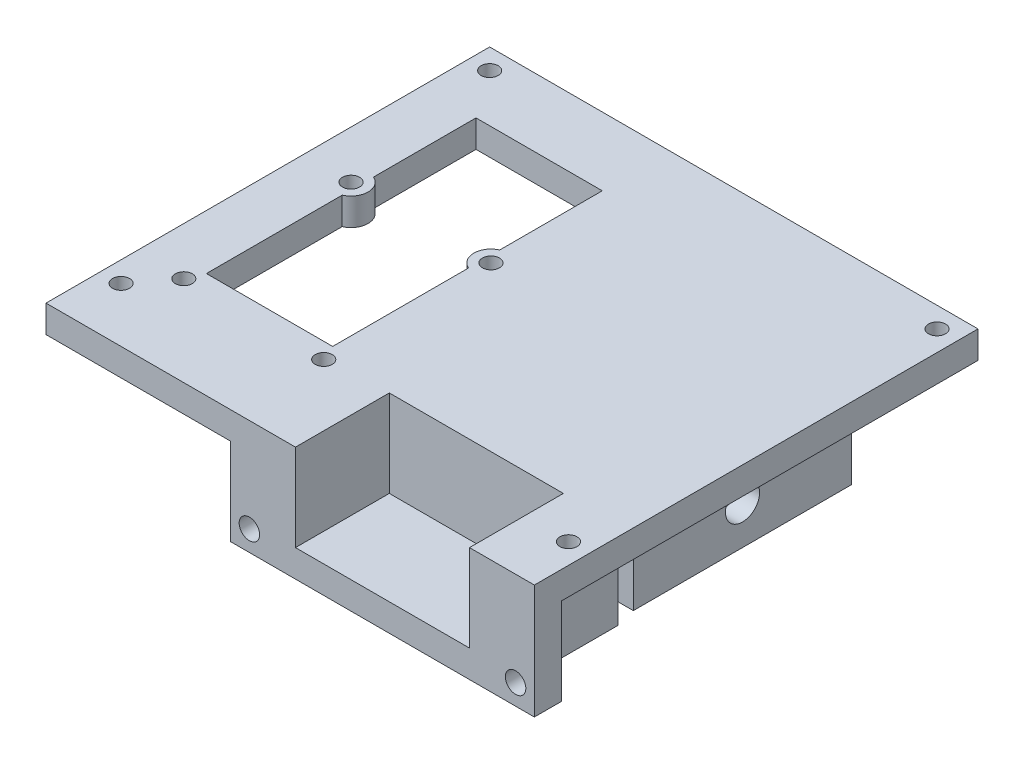
SolidWorks part; units mm, degrees
ref_plane "Front Plane" through (0, 0, 0) normal (0, 0, 1) x (1, 0, 0)
ref_plane "Top Plane" through (0, 0, 0) normal (0, 1, 0) x (1, 0, 0)
ref_plane "Right Plane" through (0, 0, 0) normal (1, 0, 0) x (0, 0, -1)
sketch "Sketch1" plane through (0, 0, 0) normal (0, 1, 0) x (1, 0, 0)
  line L1 (0, 0) -> (36.55, 0)
  line L2 (0, 0) -> (0, 65)
  line L4 (71.55, 0) -> (71.55, 65)
  line L9 (0, 65) -> (71.55, 65)
  line L11 (62.05, 0) -> (62.05, 13.75)
  line L12 (62.05, 13.75) -> (36.55, 13.75)
  line L13 (36.55, 0) -> (36.55, 13.75)
  line L14 (62.05, 0) -> (71.55, 0)
  dimension "D1" = 65
  dimension "D2" = 71.55
  dimension "D3" = 9.5
  dimension "D4" = 13.75
  dimension "D5" = 25.5
extrude "Boss-Extrude1" add sketch "Sketch1" along normal blind 4
sketch "Sketch2" plane through (0, 0, 0) normal (0, 1, 0) x (1, 0, 0)
  line L0 (62.05, 13.75) -> (62.05, 0) construction
  line L1 (36.55, 13.75) -> (62.05, 13.75) construction
  line L2 (36.55, 0) -> (36.55, 13.75) construction
  line L3 (62.05, 13.75) -> (62.05, 0)
  line L4 (36.55, 13.75) -> (62.05, 13.75)
  line L5 (36.55, 0) -> (36.55, 13.75)
  line L6 (32.55, 0) -> (32.55, 17.75)
  line L7 (32.55, 17.75) -> (66.05, 17.75)
  line L8 (66.05, 17.75) -> (66.05, 0)
  line L9 (36.55, 0) -> (32.55, 0)
  line L10 (62.05, 0) -> (66.05, 0)
  dimension "D1" = 4
extrude "Boss-Extrude2" add sketch "Sketch2" against normal blind 8.75
sketch "Sketch3" plane through (0, -8.75, 0) normal (0, -1, 0) x (1, 0, 0)
  line L1 (32.55, -17.75) -> (66.05, -17.75)
  line L2 (32.55, -17.75) -> (32.55, 0)
  line L3 (32.55, 0) -> (66.05, 0)
  line L4 (66.05, -17.75) -> (66.05, 0)
extrude "Boss-Extrude3" add sketch "Sketch3" along normal blind 4
sketch "Sketch4" plane through (0, 4, 0) normal (0, 1, 0) x (1, 0, 0)
  line L0 (0, 65) -> (0, 0) construction
  line L1 (8, 15.5) -> (26.5, 15.5)
  line L2 (8, 15.5) -> (8, 55)
  line L3 (8, 55) -> (26.5, 55)
  line L4 (26.5, 15.5) -> (26.5, 55)
  line L5 (71.55, 65) -> (0, 65) construction
  line L6 (0, 0) -> (36.55, 0) construction
  dimension "D1" = 8
  dimension "D2" = 10
  dimension "D3" = 15.5
  dimension "D4" = 18.5
extrude "Cut-Extrude1" cut sketch "Sketch4" against normal blind 4
sketch "Sketch5" plane through (0, 0, 0) normal (0, 0, 1) x (1, 0, 0)
  line L0 (66.05, -12.75) -> (32.55, -12.75) construction
  line L1 (32.55, 0) -> (27.05, 0)
  line L2 (32.55, 0) -> (32.55, -12.75)
  line L3 (32.55, -12.75) -> (27.05, -12.75)
  line L4 (27.05, 0) -> (27.05, -12.75)
  line L6 (71.55, 0) -> (66.05, 0)
  line L7 (71.55, 0) -> (71.55, -12.75)
  line L8 (71.55, -12.75) -> (66.05, -12.75)
  line L9 (66.05, 0) -> (66.05, -12.75)
  dimension "D1" = 44.5
extrude "Boss-Extrude4" add sketch "Sketch5" against normal blind 4
sketch "Sketch6" plane through (0, 0, 0) normal (0, -1, 0) x (1, 0, 0)
  line L2 (17.25, -15.5) -> (17.25, -9.6698)
  line L3 (8, -15.5) -> (26.5, -15.5) construction
  circle A0 centre (7, -13.19) radius 1.25
  circle A1 centre (27.5, -13.19) radius 1.25
  circle A2 centre (27.5, -37.69) radius 1.25
  circle A3 centre (7, -37.69) radius 1.25
  line M16 (8, -55) -> (8, -15.5)
  line M18 (26.5, -15.5) -> (26.5, -55)
  dimension "D1" = 2.5
  dimension "D4" = 20.5
  dimension "D5" = 10.25
  dimension "D6" = 2.31
  dimension "D2" = 2
  dimension "D3" = 2
extrude "Cut-Extrude2" cut sketch "Sketch6" against normal through all both and the other way through all contours A0 | A1 | A2 M18 | A3 M16
sketch "Sketch7" plane through (0, 0, 0) normal (0, -1, 0) x (1, 0, 0)
  circle A0 centre (7, -37.69) radius 1.25
  circle A1 centre (7, -37.69) radius 2.5
  circle A2 centre (27.5, -37.69) radius 1.25
  circle A3 centre (27.5, -37.69) radius 2.5
extrude "Boss-Extrude5" add sketch "Sketch7" against normal up to surface (4 mm away) up to face at (27.5, 4, -14.44)
sketch "Sketch8" plane through (0, 4, 0) normal (0, 1, 0) x (1, 0, 0)
  line L0 (71.55, 65) -> (0, 65) construction
  line L1 (0, 65) -> (0, 0) construction
  line L2 (71.55, 0) -> (71.55, 65) construction
  line L3 (62.05, 0) -> (71.55, 0) construction
  circle A0 centre (3, 62) radius 1.25
  circle A1 centre (68.55, 62) radius 1.25
  circle A2 centre (68.55, 8) radius 1.25
  circle A3 centre (3, 8) radius 1.25
  dimension "D3" = 2.5
  dimension "D1" = 3
  dimension "D2" = 3
  dimension "D6" = 3
  dimension "D7" = 8
  dimension "D4" = 2
  dimension "D5" = 2
extrude "Cut-Extrude3" cut sketch "Sketch8" against normal through all both and the other way through all
sketch "Sketch9" plane through (0, 0, -4) normal (0, 0, -1) x (-1, 0, 0)
  line L0 (-68.8, 0) -> (-68.8, -5.5114)
  line L1 (-71.55, 0) -> (-66.05, 0) construction
  line L2 (-66.05, -12.75) -> (-71.55, -12.75) construction
  line L3 (-49.3, 0) -> (-49.3, -10.27)
  line L4 (-66.05, 0) -> (-32.55, 0) construction
  circle A0 centre (-68.8, -9.75) radius 1.5
  circle A1 centre (-29.8, -9.75) radius 1.5
  dimension "D1" = 3
  dimension "D2" = 0
  dimension "D3" = 3
extrude "Cut-Extrude4" cut sketch "Sketch9" against normal through all both and the other way through all contours A0 | A1
sketch "Sketch10" plane through (0, 4, 0) normal (0, 1, 0) x (1, 0, 0)
  line L0 (71.55, 0) -> (71.55, 65) construction
  line L1 (71.55, 65) -> (0, 65) construction
  circle A0 centre (35.55, 22) radius 1
  circle A1 centre (63.55, 22) radius 1
  circle A2 centre (63.55, 59) radius 1
  circle A3 centre (35.55, 59) radius 1
  dimension "D1" = 2
  dimension "D4" = 8
  dimension "D5" = 6
  dimension "D2" = 2
  dimension "D3" = 2
extrude "Cut-Extrude5" [suppressed] cut sketch "Sketch10" against normal blind 10
sketch "Sketch11" plane through (0, 0, 0) normal (0, -1, 0) x (1, 0, 0)
  line L0 (66.05, -17.75) -> (32.55, -17.75) construction
  line L1 (33.3, -20.75) -> (65.3, -20.75)
  line L2 (33.3, -20.75) -> (33.3, -52.75)
  line L3 (33.3, -52.75) -> (65.3, -52.75)
  line L4 (65.3, -20.75) -> (65.3, -52.75)
  line L5 (32.55, -17.75) -> (66.05, -17.75) construction
  line L7 (62.3, -49.75) -> (36.3, -49.75)
  line L8 (62.3, -49.75) -> (62.3, -23.75)
  line L9 (62.3, -23.75) -> (36.3, -23.75)
  line L10 (36.3, -49.75) -> (36.3, -23.75)
  point P6 (49.3, -17.75)
  dimension "D1" = 32
  dimension "D2" = 32
  dimension "D3" = 16
  dimension "D4" = 3
  dimension "D5" = 26
  dimension "D6" = 26
  dimension "D7" = 3
  dimension "D8" = 3
extrude "Boss-Extrude6" add sketch "Sketch11" along normal up to surface (12.75 mm away) up to face at (49.3, -12.75, -6.4375)
sketch "Sketch12" plane through (65.3, 0, 0) normal (1, 0, 0) x (0, 0, -1)
  line L0 (36.75, 0) -> (36.75, -17.5222)
  line L1 (52.75, 0) -> (20.75, 0) construction
  line L3 (4, 0) -> (65, 0) construction
  circle A0 centre (36.75, -7) radius 2.5
  dimension "D1" = 5
  dimension "D2" = 7
extrude "Cut-Extrude6" cut sketch "Sketch12" against normal through all both and the other way through all contours L0 A0 | L0 A0
sketch "Sketch13" plane through (0, 0, -52.75) normal (0, 0, -1) x (-1, 0, 0)
  line L0 (-49.3, 0) -> (-49.3, -16.7046)
  line L1 (-33.3, 0) -> (-65.3, 0) construction
  circle A0 centre (-49.3, -7) radius 2.5
  dimension "D1" = 5
  dimension "D2" = 7
extrude "Cut-Extrude7" cut sketch "Sketch13" against normal blind 5 and the other way through all contours L0 A0 | L0 A0
